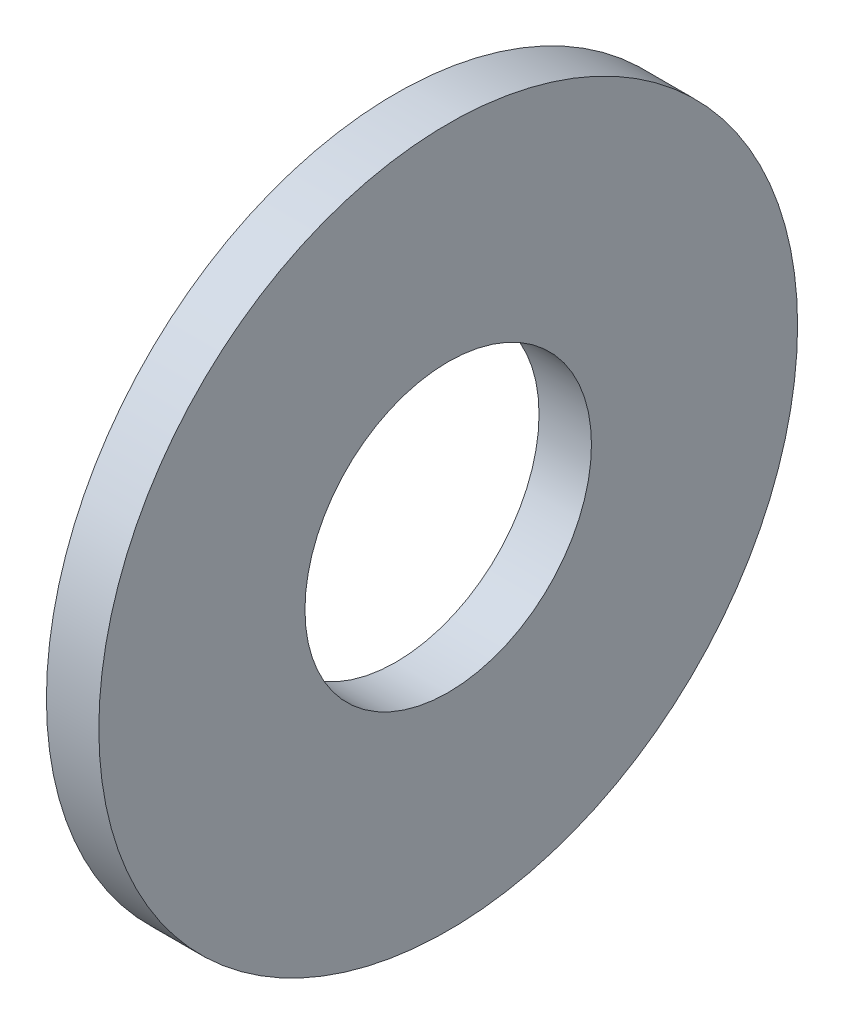
SolidWorks part; units mm, degrees
ref_plane "Front Plane" through (0, 0, 0) normal (0, 0, 1) x (1, 0, 0)
ref_plane "Top Plane" through (0, 0, 0) normal (0, 1, 0) x (1, 0, 0)
ref_plane "Right Plane" through (0, 0, 0) normal (1, 0, 0) x (0, 0, -1)
sketch "Sketch1" plane through (0, 0, 0) normal (0, 1, 0) x (1, 0, 0)
  line L0 (-0.7126, 4.1) -> (0.7874, 4.1)
  line L1 (-0.7126, 10) -> (0.7874, 10)
  line L2 (-0.7126, 10) -> (-0.7126, 4.1)
  line L3 (-0.7874, 0) -> (0.7874, 0) construction
  line L4 (0.7874, 10) -> (0.7874, 4.1)
  dimension "D1" = 10
  dimension "D2" = 1.5
  dimension "D3" = 4.1
revolve "Revolve1" add sketch "Sketch1" angle 360 about L3
